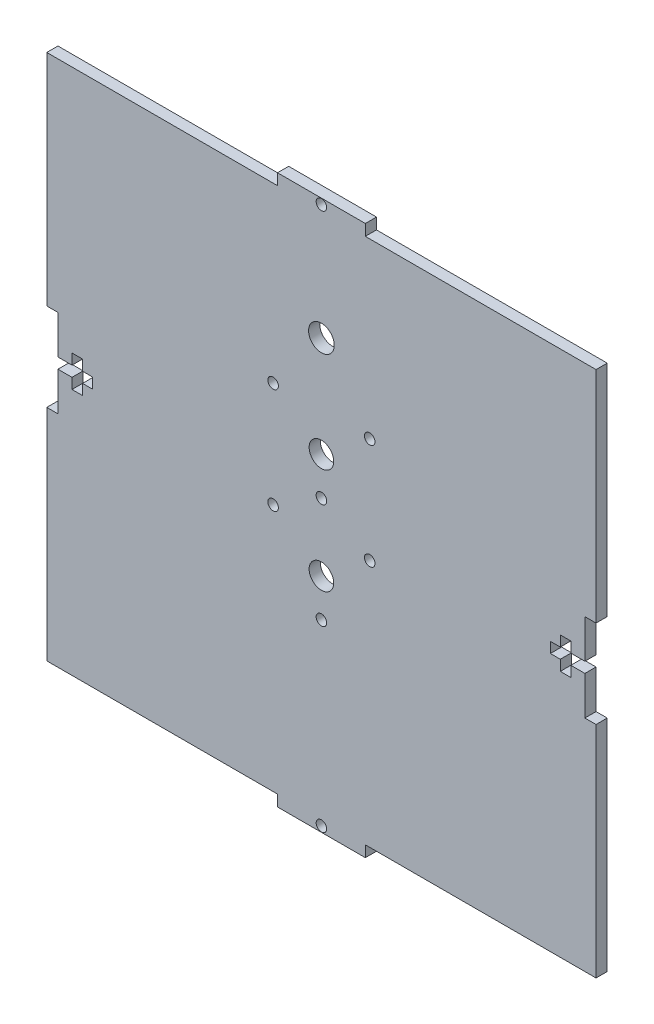
SolidWorks part; units mm, degrees
ref_plane "Front Plane" through (0, 0, 0) normal (0, 0, 1) x (1, 0, 0)
ref_plane "Top Plane" through (0, 0, 0) normal (0, 1, 0) x (1, 0, 0)
ref_plane "Right Plane" through (0, 0, 0) normal (1, 0, 0) x (0, 0, -1)
sketch "Sketch1" plane through (0, 0, 0) normal (0, 0, 1) x (1, 0, 0)
  line L0 (-12.5, 25) -> (12.5, 25) construction
  line L1 (-78.18, 75) -> (-12.5, 75)
  line L2 (-78.18, 75) -> (-78.18, 12.5)
  line L3 (-78.18, -75) -> (-12.5, -75)
  line L4 (78.18, 75) -> (78.18, 12.5)
  line L5 (-78.18, 75) -> (78.18, -75) construction
  line L6 (-78.18, -75) -> (78.18, 75) construction
  line L11 (12.5, 75) -> (12.5, 78.18)
  line L12 (12.5, 78.18) -> (-12.5, 78.18)
  line L17 (-12.5, 75) -> (-12.5, 78.18)
  line L18 (12.5, 75) -> (78.18, 75)
  line L25 (0, 100) -> (0, -75) construction
  line L26 (-100, 0) -> (100, 0) construction
  line L27 (-75, -1.5) -> (-75, -12.5)
  line L28 (-75, 12.5) -> (-78.18, 12.5)
  line L29 (-75, 12.5) -> (-75, 1.5)
  line L30 (-75, -12.5) -> (-78.18, -12.5)
  line L32 (-75, 12.5) -> (-78.18, -12.5) construction
  line L33 (-75, -12.5) -> (-78.18, 12.5) construction
  line L34 (-65.18, 1.5) -> (-68, 1.5)
  line L35 (-65.18, 1.5) -> (-65.18, -1.5)
  line L36 (-65.18, -1.5) -> (-68, -1.5)
  line L38 (-65.18, 1.5) -> (-75, -1.5) construction
  line L39 (-65.18, -1.5) -> (-75, 1.5) construction
  line L44 (-71, 4.5) -> (-68, 4.5)
  line L45 (-71, 4.5) -> (-71, 1.5)
  line L46 (-71, -4.5) -> (-68, -4.5)
  line L47 (-68, 4.5) -> (-68, 1.5)
  line L48 (-71, 4.5) -> (-68, -4.5) construction
  line L49 (-71, -4.5) -> (-68, 4.5) construction
  line L50 (-71, -1.5) -> (-71, -4.5)
  line L51 (-68, -1.5) -> (-68, -4.5)
  line L52 (-71, 1.5) -> (-75, 1.5)
  line L53 (-71, -1.5) -> (-75, -1.5)
  line L54 (65.18, 1.5) -> (68, 1.5)
  line L55 (68, 4.5) -> (68, 1.5)
  line L56 (71, 4.5) -> (68, 4.5)
  line L57 (71, 4.5) -> (71, 1.5)
  line L58 (71, 1.5) -> (75, 1.5)
  line L59 (75, 12.5) -> (75, 1.5)
  line L60 (75, 12.5) -> (78.18, 12.5)
  line L62 (75, -12.5) -> (78.18, -12.5)
  line L63 (75, -1.5) -> (75, -12.5)
  line L64 (71, -1.5) -> (75, -1.5)
  line L65 (71, -1.5) -> (71, -4.5)
  line L66 (71, -4.5) -> (68, -4.5)
  line L67 (68, -1.5) -> (68, -4.5)
  line L68 (65.18, -1.5) -> (68, -1.5)
  line L69 (65.18, 1.5) -> (65.18, -1.5)
  line L70 (-78.18, -12.5) -> (-78.18, -75)
  line L71 (78.18, -12.5) -> (78.18, -75)
  line L72 (0, -78.18) -> (0, -75) construction
  line L74 (12.5, -75) -> (12.5, -78.18)
  line L75 (12.5, -78.18) -> (-12.5, -78.18)
  line L76 (-12.5, -75) -> (-12.5, -78.18)
  line L77 (12.5, -76.59) -> (-12.5, -76.59) construction
  line L78 (12.5, -75) -> (78.18, -75)
  circle A2 centre (0, -76.59) radius 1.5
  circle A3 centre (0, 76.59) radius 1.5
  point P0 (0, 0)
  point P6 (-50, 50)
  point P11 (50, 50)
  point P16 (0, 0)
  point P27 (0, 25)
  point P30 (-76.59, 0)
  point P35 (-70.09, 0)
  point P40 (-70.09, 0)
  point P41 (-69.5, 0)
  dimension "D13" = 25
  dimension "D23" = 3
  dimension "D1" = 150
  dimension "D2" = 156.36
  dimension "D3" = 9
  dimension "D9" = 50
  dimension "D10" = 50
  dimension "D14" = 50
  dimension "D15" = 25
  dimension "D16" = 13
  dimension "D17" = 3.18
  dimension "D18" = 3
  dimension "D19" = 4
  dimension "D20" = 3
  dimension "D21" = 3.18
  dimension "D22" = 25
extrude "Boss-Extrude1" add sketch "Sketch1" along normal blind 3.18
sketch "Sketch2" plane through (0, 0, 3.18) normal (0, 0, 1) x (1, 0, 0)
  circle A0 centre (-13.75, -4.3) radius 1.5
  circle A1 centre (0, -25.8) radius 1.5
  circle A2 centre (13.75, -4.3) radius 1.5
  circle A3 centre (0, 4.2) radius 1.5
  circle A4 centre (13.75, 25.7) radius 1.5
  circle A5 centre (-13.75, 25.7) radius 1.5
  circle A6 centre (0, 15) radius 3.5
  circle A7 centre (0, -15) radius 3.5
  dimension "D1" = 3
  dimension "D2" = 3
  dimension "D3" = 3
  dimension "D4" = 3
  dimension "D5" = 3
  dimension "D6" = 3
  dimension "D7" = 7
  dimension "D8" = 7
extrude "Cut-Extrude1" cut sketch "Sketch2" against normal blind 10
sketch "Sketch3" plane through (0, 0, 0) normal (0, 0, -1) x (-1, 0, 0)
  circle A0 centre (0, 43.7) radius 3.6561
extrude "Cut-Extrude2" cut sketch "Sketch3" against normal blind 10
